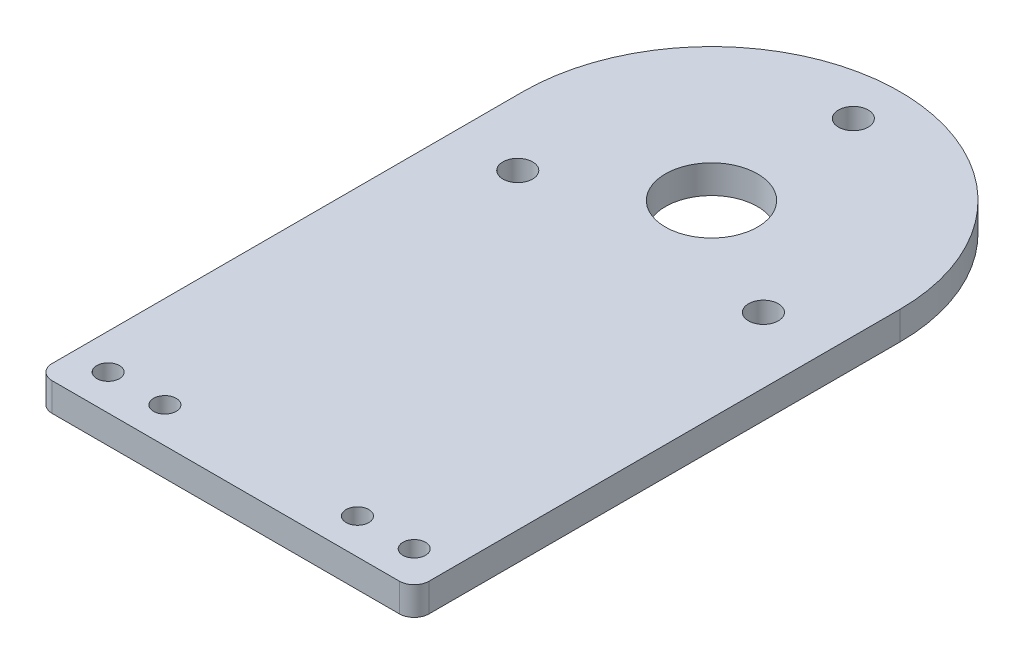
SolidWorks part; units mm, degrees
ref_plane "前视基准面" through (0, 0, 0) normal (0, 0, 1) x (1, 0, 0)
ref_plane "上视基准面" through (0, 0, 0) normal (0, 1, 0) x (1, 0, 0)
ref_plane "右视基准面" through (0, 0, 0) normal (1, 0, 0) x (0, 0, -1)
sketch "草图1" plane through (0, 0, 0) normal (0, 1, 0) x (1, 0, 0)
  line L0 (-26.5803, -66.4044) -> (-26.5803, 0)
  line L1 (26.5803, 0) -> (26.5803, -66.4044)
  line L2 (-24.4803, -68.5044) -> (24.4803, -68.5044)
  line L3 (0, -6.5) -> (0, -68.5044) construction
  circle A0 centre (0, 0) radius 6.5
  arc A1 (24.4803, -68.5044) -> (26.5803, -66.4044) centre (24.4803, -66.4044) ccw
  circle A2 centre (0, 20) radius 2.1
  circle A3 centre (-17.3205, -10) radius 2.1
  circle A4 centre (17.3205, -10) radius 2.1
  arc A5 (-26.5803, 0) -> (26.5803, 0) centre (0, 0) cw
  arc A6 (-24.4803, -68.5044) -> (-26.5803, -66.4044) centre (-24.4803, -66.4044) cw
  circle A7 centre (21.5803, -63.5044) radius 1.6
  circle A8 centre (13.5803, -63.5044) radius 1.6
  circle A9 centre (-13.5803, -63.5044) radius 1.6
  circle A10 centre (-21.5803, -63.5044) radius 1.6
  dimension "D2" = 13
  dimension "D3" = 26.5803
  dimension "D5" = 5
  dimension "D6" = 34.641
  dimension "D7" = 3.2
  dimension "D8" = 17.3205
  dimension "D9" = 20
  dimension "D11" = 8
  dimension "D12" = 4.2
  dimension "D10" = 10
  dimension "D13" = 68.5044
  dimension "D4" = 5
extrude "凸台-拉伸2" add sketch "草图1" along normal blind 4
